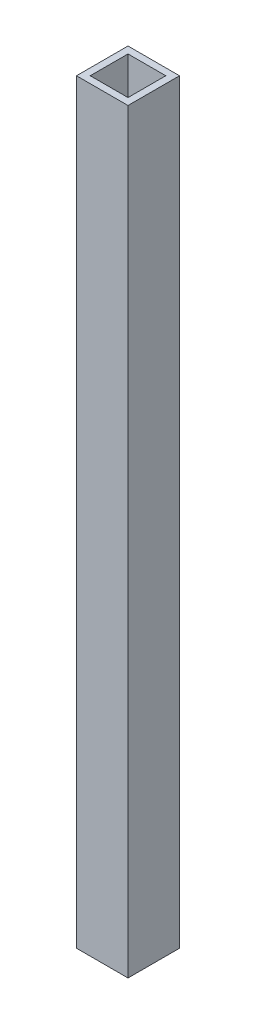
SolidWorks part; units mm, degrees
ref_plane "Front Plane" through (0, 0, 0) normal (0, 0, 1) x (1, 0, 0)
ref_plane "Top Plane" through (0, 0, 0) normal (0, 1, 0) x (1, 0, 0)
ref_plane "Right Plane" through (0, 0, 0) normal (1, 0, 0) x (0, 0, -1)
sketch "Sketch1" plane through (0, 0, 0) normal (0, 1, 0) x (1, 0, 0)
  line L0 (2, 2) -> (2, 13)
  line L1 (0, 0) -> (15, 0)
  line L2 (0, 0) -> (0, 15)
  line L3 (0, 15) -> (15, 15)
  line L4 (15, 0) -> (15, 15)
  line L5 (2, 13) -> (13, 13)
  line L6 (13, 2) -> (13, 13)
  line L7 (2, 2) -> (13, 2)
  dimension "D1" = 15
  dimension "D2" = 2
extrude "Boss-Extrude1" add sketch "Sketch1" along normal blind 220
